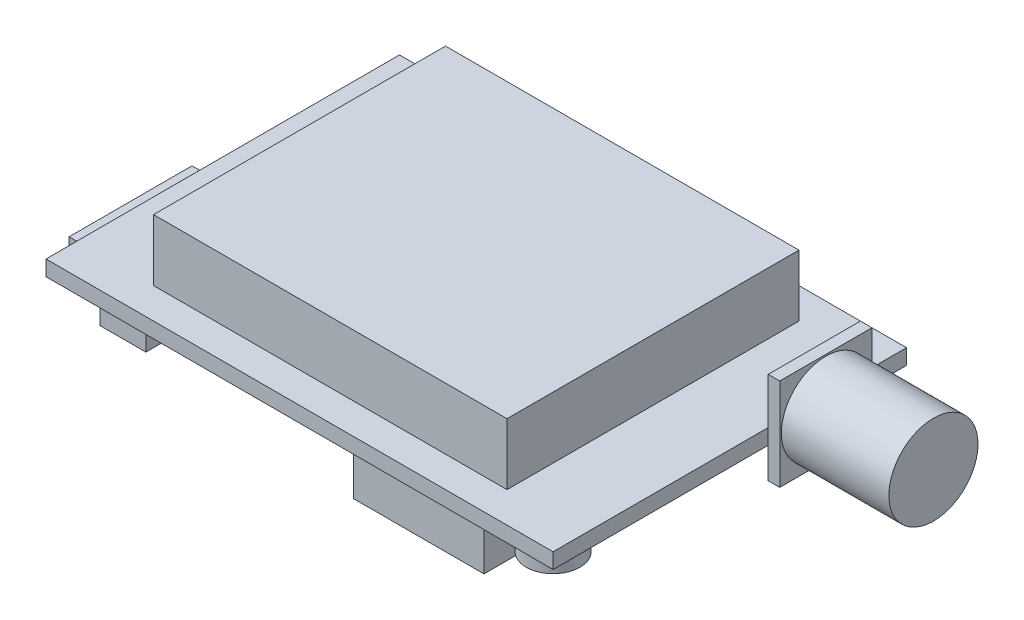
SolidWorks part; units mm, degrees
ref_plane "Front Plane" through (0, 0, 0) normal (0, 0, 1) x (1, 0, 0)
ref_plane "Top Plane" through (0, 0, 0) normal (0, 1, 0) x (1, 0, 0)
ref_plane "Right Plane" through (0, 0, 0) normal (1, 0, 0) x (0, 0, -1)
sketch "Sketch1" plane through (0, 0, 0) normal (0, 1, 0) x (1, 0, 0)
  line L1 (-22.4, 9.5) -> (10.6, 9.5)
  line L2 (-22.4, 9.5) -> (-22.4, -13.5)
  line L3 (-22.4, -13.5) -> (10.6, -13.5)
  line L4 (10.6, 9.5) -> (10.6, -13.5)
  dimension "D1" = 23
  dimension "D2" = 33
extrude "Boss-Extrude1" add sketch "Sketch1" along normal blind 1
sketch "Sketch2" plane through (0, 1, 0) normal (0, 1, 0) x (1, 0, 0)
  line L0 (-22.4, -13.5) -> (10.6, -13.5) construction
  line L1 (-17.4, 7.5) -> (5.6, 7.5)
  line L2 (-17.4, 7.5) -> (-17.4, -11.5)
  line L3 (-17.4, -11.5) -> (5.6, -11.5)
  line L4 (5.6, 7.5) -> (5.6, -11.5)
  line L5 (10.6, 9.5) -> (-22.4, 9.5) construction
  line L6 (-22.4, 9.5) -> (-22.4, -13.5) construction
  line L7 (10.6, -13.5) -> (10.6, 9.5) construction
  dimension "D1" = 2
  dimension "D2" = 2
  dimension "D3" = 5
  dimension "D4" = 5
extrude "Boss-Extrude2" add sketch "Sketch2" along normal blind 4
sketch "Sketch3" plane through (0, 0, 0) normal (0, -1, 0) x (-1, 0, 0)
  line L6 (22.4, -13.5) -> (-10.6, -13.5) construction
  line L7 (2.9, -13) -> (-5.6, -13)
  line L8 (2.9, -13) -> (2.9, -6)
  line L9 (2.9, -6) -> (-5.6, -6)
  line L10 (-5.6, -13) -> (-5.6, -6)
  line L11 (-10.6, -13.5) -> (-10.6, 9.5) construction
  dimension "D1" = 7
  dimension "D2" = 8.5
  dimension "D3" = 0.5
  dimension "D4" = 5
extrude "Boss-Extrude4" add sketch "Sketch3" along normal blind 3
sketch "Sketch4" plane through (0, 0, 0) normal (0, -1, 0) x (1, 0, 0)
  line L0 (10.6, 13.5) -> (10.6, -9.5) construction
  line L1 (-22.4, 13.5) -> (10.6, 13.5) construction
  circle A0 centre (8.6, 11.5) radius 1.75
  dimension "D1" = 3.5
  dimension "D2" = 2
  dimension "D3" = 2
extrude "Boss-Extrude5" add sketch "Sketch4" along normal blind 1
sketch "Sketch5" plane through (10.6, 0, 0) normal (1, 0, 0) x (0, 0, -1)
  line L1 (6.5, 4) -> (0.5, 4)
  line L2 (6.5, 4) -> (6.5, -2)
  line L3 (6.5, -2) -> (0.5, -2)
  line L4 (0.5, 4) -> (0.5, -2)
  line L5 (-13.5, 1) -> (9.5, 1) construction
  line L6 (9.5, 1) -> (9.5, 0) construction
  point P8 (9.5, 0.5)
  dimension "D1" = 6
  dimension "D2" = 3
  dimension "D3" = 3
extrude "Boss-Extrude6" add sketch "Sketch5" along normal blind 0.75
sketch "Sketch6" plane through (11.35, 0, 0) normal (1, 0, 0) x (0, 0, -1)
  line L0 (6.5, 4) -> (0.5, -2) construction
  line L1 (0.5, -2) -> (6.5, -2) construction
  line L2 (0.5, 4) -> (0.5, -2) construction
  line L3 (0.5, 4) -> (6.5, -2) construction
  circle A1 centre (3.5, 1) radius 2.9
  dimension "D1" = 5.8
extrude "Boss-Extrude7" add sketch "Sketch6" along normal blind 7
sketch "Sketch7" plane through (0, 0, 0) normal (0, -1, 0) x (-1, 0, 0)
  line L0 (-10.6, 9.5) -> (22.4, 9.5) construction
  line L1 (1.4, 6) -> (-4.6, 6)
  line L2 (1.4, 6) -> (1.4, 9)
  line L3 (1.4, 9) -> (-4.6, 9)
  line L4 (-4.6, 6) -> (-4.6, 9)
  line L5 (-10.6, 6.5) -> (-10.6, 9.5) construction
  dimension "D1" = 6
  dimension "D2" = 3
  dimension "D3" = 0.5
  dimension "D4" = 6
extrude "Boss-Extrude8" add sketch "Sketch7" along normal blind 1.5
sketch "Sketch8" plane through (0, -1.5, 0) normal (0, -1, 0) x (1, 0, 0)
  line L0 (1.0729, -8) -> (1.0729, -9) construction
  line L1 (-0.4, -7) -> (3.6, -7)
  line L2 (-0.4, -7) -> (-0.4, -8)
  line L3 (-0.4, -8) -> (3.6, -8)
  line L4 (3.6, -7) -> (3.6, -8)
  line L5 (-1.4, -9) -> (4.6, -9) construction
  line L6 (-0.4, -7.5) -> (-1.4, -7.5) construction
  line L7 (-1.4, -6) -> (-1.4, -9) construction
  line L8 (1.6, -7) -> (1.6, -6) construction
  line L9 (4.6, -6) -> (-1.4, -6) construction
  line L10 (3.6, -7.5) -> (4.6, -7.5) construction
  line L11 (4.6, -9) -> (4.6, -6) construction
  dimension "D1" = 4
extrude "Boss-Extrude9" add sketch "Sketch8" along normal blind 1
sketch "Sketch9" plane through (0, 0, 0) normal (0, -1, 0) x (1, 0, 0)
  line L0 (-22.4, 13.5) -> (10.6, 13.5) construction
  line L1 (-21.9, 10.5) -> (-18.9, 10.5)
  line L2 (-21.9, 10.5) -> (-21.9, 0.5)
  line L3 (-21.9, 0.5) -> (-18.9, 0.5)
  line L4 (-18.9, 10.5) -> (-18.9, 0.5)
  line L5 (-22.4, -9.5) -> (-22.4, 13.5) construction
  dimension "D1" = 10
  dimension "D2" = 3
  dimension "D3" = 3
  dimension "D4" = 0.5
extrude "Boss-Extrude10" add sketch "Sketch9" along normal blind 4
sketch "Sketch10" plane through (-21.9, 0, 0) normal (-1, 0, 0) x (0, 0, 1)
  line L0 (10.5, -4) -> (10.5, 0) construction
  line L1 (9.5, -3) -> (1.5, -3)
  line L2 (9.5, -3) -> (9.5, -1)
  line L3 (9.5, -1) -> (1.5, -1)
  line L4 (1.5, -3) -> (1.5, -1)
  line L5 (0.5, -4) -> (0.5, 0) construction
  line L6 (10.5, -4) -> (0.5, -4) construction
  line L7 (10.5, 0) -> (0.5, 0) construction
  dimension "D1" = 1
  dimension "D2" = 1
  dimension "D3" = 1
  dimension "D4" = 1
extrude "Boss-Extrude11" add sketch "Sketch10" along normal blind 3
ref_plane "Mid-Plane" through (0, 0, 2) normal (0, 0, 1) x (1, 0, 0)
